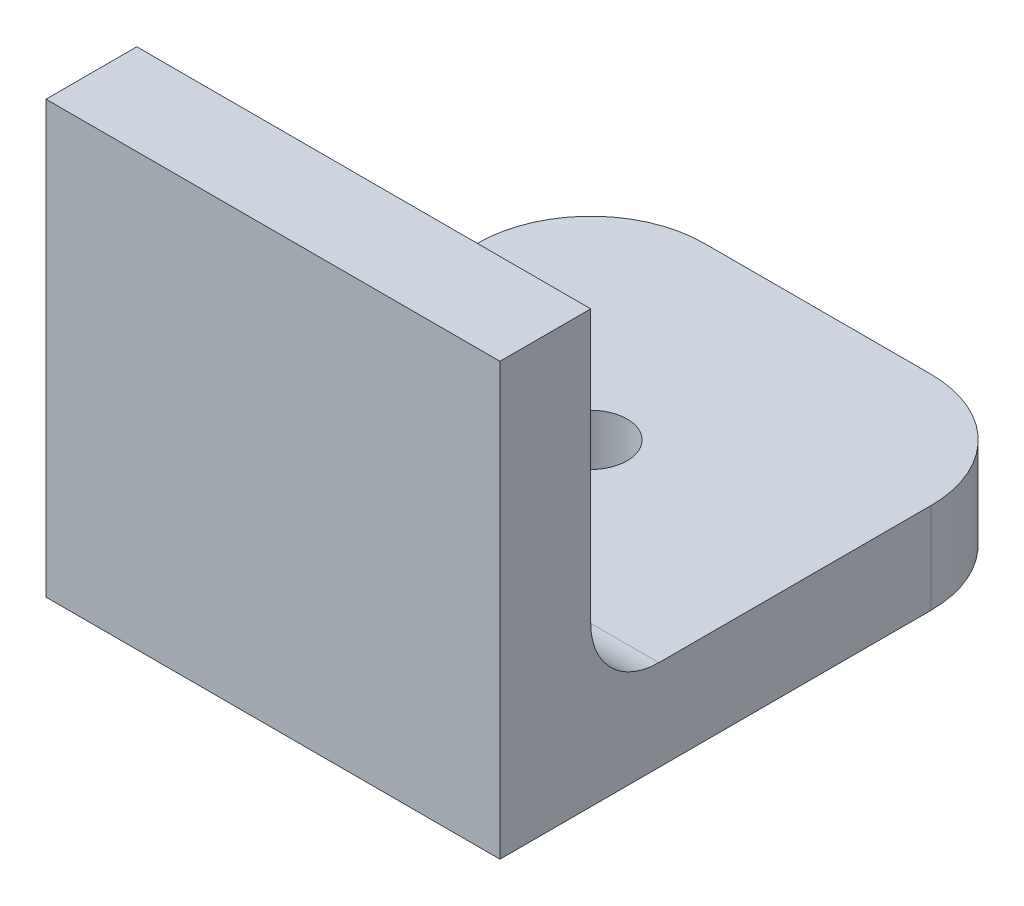
SolidWorks part; units mm, degrees
ref_plane "Front Plane" through (0, 0, 0) normal (0, 0, 1) x (1, 0, 0)
ref_plane "Top Plane" through (0, 0, 0) normal (0, 1, 0) x (1, 0, 0)
ref_plane "Right Plane" through (0, 0, 0) normal (1, 0, 0) x (0, 0, -1)
sketch "Sketch1" plane through (0, 0, 0) normal (0, 1, 0) x (1, 0, 0)
  line L1 (0, 0) -> (20, 0)
  line L2 (0, 0) -> (0, -20)
  line L3 (0, -20) -> (20, -20)
  line L4 (20, 0) -> (20, -20)
  circle A0 centre (10, -10) radius 1.6
  dimension "D3" = 3.2
  dimension "D1" = 20
  dimension "D2" = 20
extrude "Boss-Extrude1" add sketch "Sketch1" along normal blind 4
sketch "Sketch2" plane through (0, 0, 0) normal (0, -1, 0) x (-1, 0, 0)
  line L1 (0, -20) -> (-20, -20)
  line L2 (0, -20) -> (0, -24)
  line L3 (0, -24) -> (-20, -24)
  line L4 (-20, -20) -> (-20, -24)
  dimension "D1" = 20
  dimension "D2" = 4
extrude "Boss-Extrude2" add sketch "Sketch2" against normal blind 19
fillet "Fillet1" radius 3 1 edges at (10, 4, 20)
fillet "Fillet2" radius 5 2 edges at (0, 2, 0) (20, 2, 0)
equation "\"D1@Boss-Extrude2\"=9.5+8+1.5"
